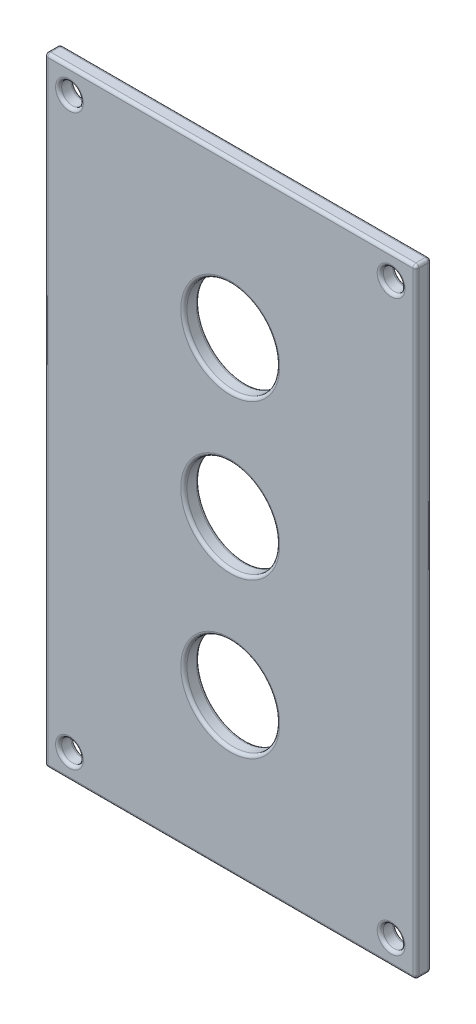
SolidWorks part; units mm, degrees
ref_plane "Alzado" through (0, 0, 0) normal (0, 0, 1) x (1, 0, 0)
ref_plane "Planta" through (0, 0, 0) normal (0, 1, 0) x (1, 0, 0)
ref_plane "Vista lateral" through (0, 0, 0) normal (1, 0, 0) x (0, 0, -1)
sketch "Croquis1" plane through (0, 0, 0) normal (0, 0, 1) x (1, 0, 0)
  line L1 (0, 0) -> (60, 0)
  line L2 (0, 0) -> (0, 100)
  line L3 (0, 100) -> (60, 100)
  line L4 (60, 0) -> (60, 100)
  line L5 (4, 4) -> (56, 4) construction
  line L6 (4, 4) -> (4, 96) construction
  line L7 (4, 96) -> (56, 96) construction
  line L8 (56, 4) -> (56, 96) construction
  circle A0 centre (4, 96) radius 1.75
  circle A1 centre (4, 4) radius 1.75
  circle A2 centre (56, 4) radius 1.75
  circle A3 centre (56, 96) radius 1.75
  point P13 (0, 0)
  point P14 (0, 0)
  dimension "D9" = 3.5
  dimension "D1" = 52
  dimension "D2" = 92
  dimension "D3" = 4
  dimension "D4" = 4
  dimension "D5" = 4
  dimension "D6" = 4
extrude "Saliente-Extruir1" add sketch "Croquis1" along normal blind 2.5
ref_plane "Plano2" through (0, 0, 2.5) normal (0, 0, 1) x (1, 0, 0)
sketch "Croquis3" plane through (0, 0, 2.5) normal (0, 0, 1) x (1, 0, 0)
  line L0 (0, 50) -> (60, 50) construction
  line L1 (0, 100) -> (0, 0) construction
  line L2 (60, 0) -> (60, 100) construction
  line L3 (30, 100) -> (30, 0) construction
  line L4 (60, 100) -> (0, 100) construction
  line L5 (0, 0) -> (60, 0) construction
  line L10 (60, 50) -> (30, 100) construction
  line L11 (45, 75) -> (30, 75) construction
  line L12 (60, 50) -> (30, 0) construction
  line L13 (45, 25) -> (30, 25) construction
  circle A4 centre (30, 50) radius 7.5
  circle A5 centre (30, 75) radius 7.5
  circle A6 centre (30, 25) radius 7.5
  dimension "D5" = 15
extrude "Cortar-Extruir1" cut sketch "Croquis3" against normal up to next
fillet "Redondeo1" radius 0.5 26 edges at (57.75, 96, 2.5) (57.75, 4, 2.5) (5.75, 4, 2.5) (5.75, 96, 2.5) (30, 100, 2.5) (60, 50, 2.5) (30, 0, 2.5) (0, 50, 2.5) (37.5, 50, 2.5) (37.5, 75, 2.5) (37.5, 25, 2.5) (57.75, 96, 0) (5.75, 4, 0) (30, 0, 0) (60, 50, 0) (30, 100, 0) (0, 50, 0) (5.75, 96, 0) (57.75, 4, 0) (22.5, 50, 0) (22.5, 75, 0) (22.5, 25, 0) (60, 100, 1.25) (0, 100, 1.25) (0, 0, 1.25) (60, 0, 1.25)
